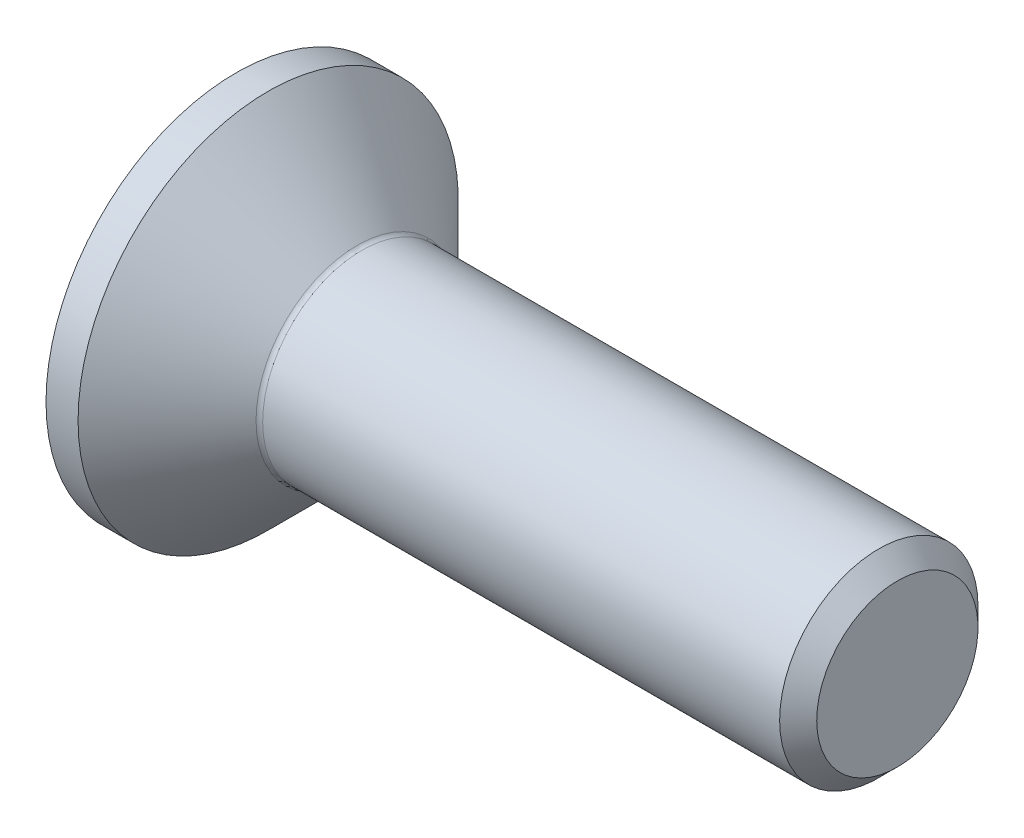
SolidWorks part; units mm, degrees
ref_plane "Plane1" through (0, 0, 0) normal (0, 0, 1) x (1, 0, 0)
ref_plane "Plane2" through (0, 0, 0) normal (0, 1, 0) x (1, 0, 0)
ref_plane "Plane3" through (0, 0, 0) normal (1, 0, 0) x (0, 0, -1)
sketch "BodySke" plane through (0, 0, 0) normal (0, 0, 1) x (1, 0, 0)
  line L0 (0, 0) -> (0, 2.875)
  line L1 (0.485, 2.875) -> (1.86, 1.5)
  line L2 (0, 2.875) -> (0.485, 2.875)
  line L3 (1.86, 1.5) -> (9.7195, 1.5)
  line L4 (10, 1.2195) -> (10, 0)
  line L5 (10, 0) -> (0, 0)
  line L6 (0, 0) -> (127, 0) construction
  line L7 (0.485, -2.875) -> (1.86, -1.5) construction
  line L8 (10, 1.2195) -> (9.7195, 1.5)
  line L9 (0, -2.875) -> (0.485, -2.875) construction
  line L10 (10, -1.2195) -> (9.7195, -1.5) construction
  line L11 (2.36, 7.85) -> (2.36, -14.375) construction
  line L12 (0, 19.05) -> (0, -3.175) construction
  dimension "D1" = 0.485
  dimension "Diameter" = 3
  dimension "Head_ht" = 1.86
  dimension "Length" = 10
  dimension "Body_ch_ang" = 45
  dimension "Head_dia" = 5.75
  dimension "Minor_dia" = 2.439
  dimension "Head_ang" = 90
  dimension "Advance" = 0.5
  dimension "Thread_nom" = 10
revolve "BaseBody" add sketch "BodySke" angle 360 about L6
cosmetic thread "ThreadCosmetic" parameters "Thread_length"=7.14, "Thread_minor"=2.439
fillet "Fillet1" radius 0.1 1 edges at (1.86, 0, 1.5)
sketch "Sketch2" plane through (0, 0, 0) normal (0, 0, 1) x (1, 0, 0)
  line L0 (0, 1) -> (1.1, 1)
  line L1 (1.1, 1) -> (1.6774, 0)
  line L2 (0, 0) -> (127, 0) construction
  line L3 (1.6774, 0) -> (0, 0)
  line L4 (0, 0) -> (0, 1)
  line L5 (0, -1) -> (1.1, -1) construction
  line L6 (0, 0) -> (47.625, 0) construction
  line L8 (0, 2.875) -> (0, -2.875) construction
  dimension "D2" = 60
  dimension "PreBroach_depth" = 1.1
  dimension "PreBroach_dia" = 2
revolve "PreBroach" cut sketch "Sketch2" angle 360 about L6
sketch "Sketch3" plane through (0, 0, 0) normal (-1, 0, 0) x (0, 0, 1)
  line L0 (-1, -0.5774) -> (-1, 0.5774)
  line L1 (-1, 0.5774) -> (0, 1.1547)
  line L2 (0, 1.1547) -> (1, 0.5774)
  line L3 (1, 0.5774) -> (1, -0.5774)
  line L4 (1, -0.5774) -> (0, -1.1547)
  line L5 (0, -1.1547) -> (-1, -0.5774)
  dimension "D1" = 1
  dimension "D2" = 1
  dimension "D3" = 2
  dimension "Hex_size" = 2
extrude "Hex" cut sketch "Sketch3" against normal blind 1.1
sketch "ThdSchSke" plane through (0, 0, 0) normal (0, 0, 1) x (1, 0, 0)
  line L0 (2.86, -1.2195) -> (2.6636, -1.5)
  line L1 (2.86, -1.2195) -> (3.0564, -1.5)
  line L2 (3.0564, -1.5) -> (3.0564, -1.875)
  line L3 (-3.175, 0) -> (5.1513, 0) construction
  line L4 (0, 2.875) -> (0, -2.875) construction
  line L5 (3.0564, -1.875) -> (2.6636, -1.875)
  line L6 (2.6636, -1.875) -> (2.6636, -1.5)
  dimension "Thread_minor" = 2.439
  dimension "Diameter" = 3
  dimension "Start" = 2.86
  dimension "SideAngle" = 55
  dimension "VeeAngle" = 70
  dimension "Overcut" = 3.75
revolve "ThreadSchematic" [suppressed] cut sketch "ThdSchSke" angle 360 about L3
pattern_linear "ThdSchPat" [suppressed]
equation "\"Thread_minor@ThreadCosmetic\"  =  \"Minor_dia@BodySke\""
equation "\"D1@Sketch3\" = \"Hex_size@Sketch3\" / 2"
equation "\"D2@Sketch3\" = \"D1@Sketch3\""
equation "\"D3@Sketch3\" = \"Hex_size@Sketch3\""
equation "\"Thread_length@ThreadCosmetic\" = ((sgn( (\"Length@BodySke\" - \"Advance@BodySke\" * 2.0 - \"Head_ht@BodySke\" ) - \"Thread_nom@BodySke\" )-1)*( (\"Length@BodySke\" - \"Advance@BodySke\" * 2.0 - \"Head_ht@BodySke\" ) - \"Thread_nom@BodySke\" ))/-2+ \"Thread_nom@BodySke\""
equation "\"Thread_minor@ThdSchSke\" = \"Minor_dia@BodySke\""
equation "\"Diameter@ThdSchSke\" = \"Diameter@BodySke\""
equation "\"Overcut@ThdSchSke\" = \"Diameter@BodySke\" * 1.25"
equation "\"Start@ThdSchSke\" = 0.000001 + \"Length@BodySke\" - \"Thread_length@ThreadCosmetic\"  '---Countersunk---"
equation "\"Num_threads@ThdSchPat\" = int( \"Thread_length@ThreadCosmetic\" / \"Advance@BodySke\" + 0.999 )  + 1"
equation "\"Advance@ThdSchPat\" = \"Thread_length@ThreadCosmetic\" /  (\"Num_threads@ThdSchPat\" - 1) 'relax it"
equation "\"Num_threads@ThdSchPat\" = \"Num_threads@ThdSchPat\" - sgn( \"Num_threads@ThdSchPat\" - 1) '---chamfered tips only---"
